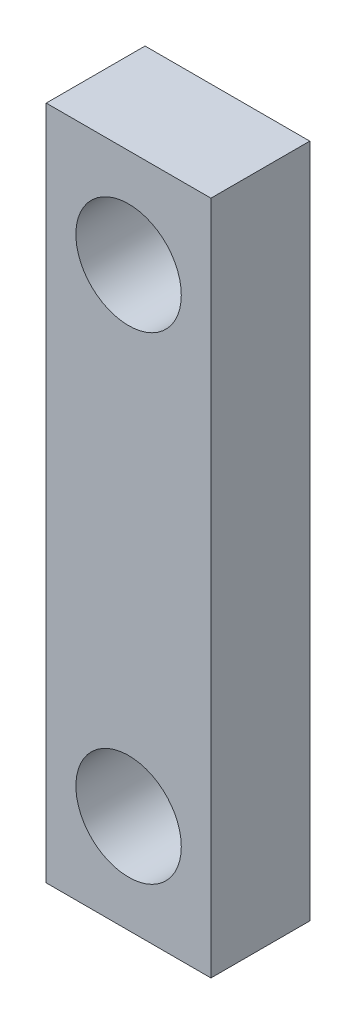
SolidWorks part; units mm, degrees
ref_plane "Front Plane" through (0, 0, 0) normal (0, 0, 1) x (1, 0, 0)
ref_plane "Top Plane" through (0, 0, 0) normal (0, 1, 0) x (1, 0, 0)
ref_plane "Right Plane" through (0, 0, 0) normal (1, 0, 0) x (0, 0, -1)
sketch "Sketch1" plane through (0, 0, 0) normal (0, 0, 1) x (1, 0, 0)
  line L1 (-2.5, -10.25) -> (2.5, -10.25)
  line L2 (-2.5, -10.25) -> (-2.5, 10.25)
  line L3 (-2.5, 10.25) -> (2.5, 10.25)
  line L4 (2.5, -10.25) -> (2.5, 10.25)
  line L5 (0, 10.25) -> (0, -10.25) construction
  line L6 (-2.5, 0) -> (2.5, 0) construction
  circle A0 centre (0, -7.25) radius 1.6
  circle A1 centre (0, 7.25) radius 1.6
  point P0 (0, 0)
  dimension "D3" = 3.2
  dimension "D6" = 3.2
  dimension "D1" = 5
  dimension "D2" = 20.5
  dimension "D4" = 3
  dimension "D5" = 14.5
extrude "Boss-Extrude1" add sketch "Sketch1" along normal blind 3
